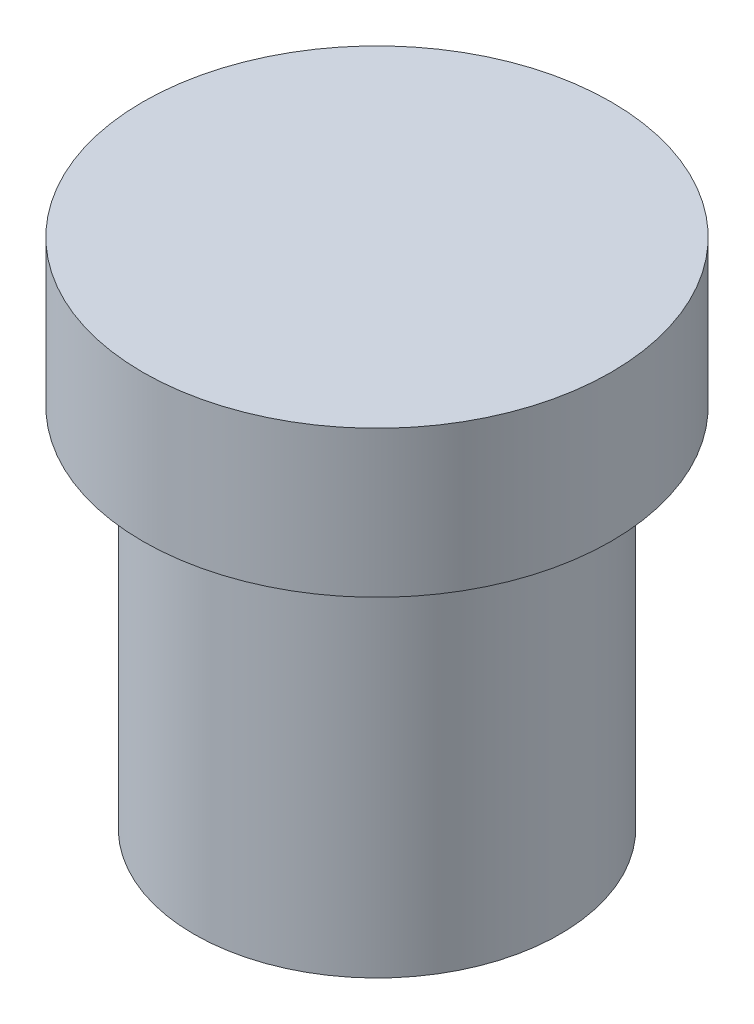
SolidWorks part; units mm, degrees
ref_plane "Спереди" through (0, 0, 0) normal (0, 0, 1) x (1, 0, 0)
ref_plane "Сверху" through (0, 0, 0) normal (0, 1, 0) x (1, 0, 0)
ref_plane "Справа" through (0, 0, 0) normal (1, 0, 0) x (0, 0, -1)
sketch "Эскиз1" plane through (0, 0, 0) normal (0, 1, 0) x (1, 0, 0)
  circle A0 centre (0, 0) radius 2.5
extrude "Бобышка-Вытянуть1" add sketch "Эскиз1" along normal blind 5
sketch "Эскиз2" plane through (0, 5, 0) normal (0, 1, 0) x (1, 0, 0)
  circle A0 centre (0, 0) radius 3.2
extrude "Бобышка-Вытянуть2" add sketch "Эскиз2" along normal blind 2
